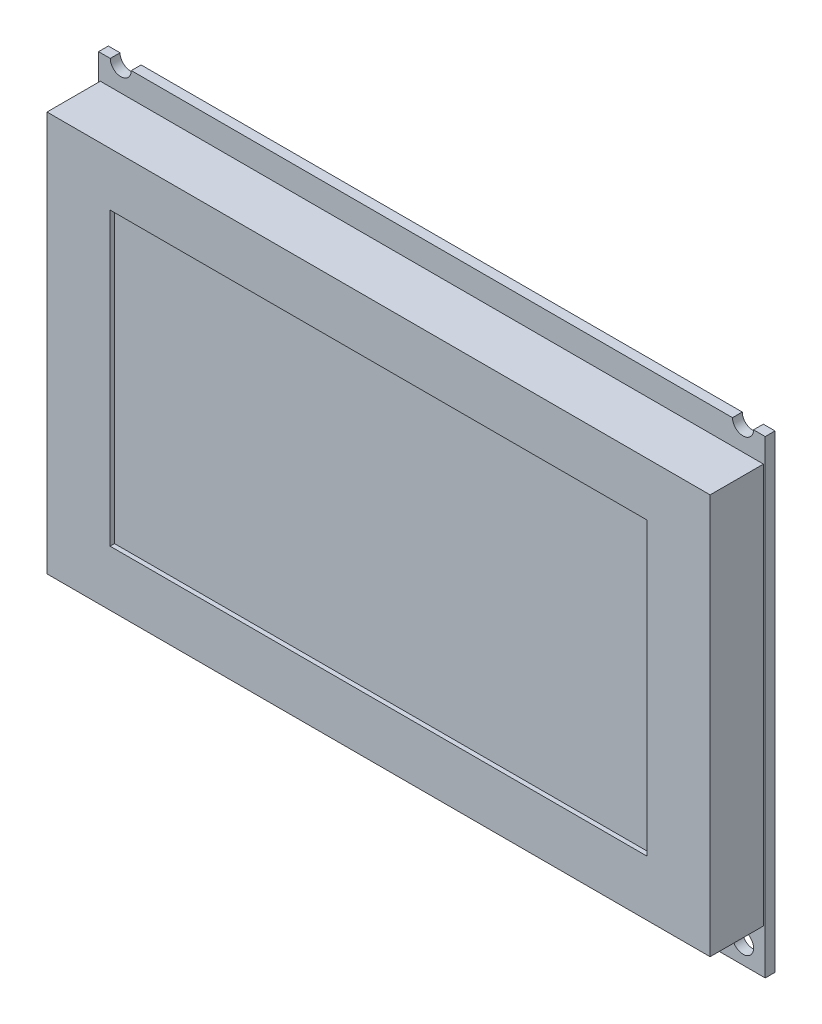
SolidWorks part; units mm, degrees
ref_plane "Front Plane" through (0, 0, 0) normal (0, 0, 1) x (1, 0, 0)
ref_plane "Top Plane" through (0, 0, 0) normal (0, 1, 0) x (1, 0, 0)
ref_plane "Right Plane" through (0, 0, 0) normal (1, 0, 0) x (0, 0, -1)
sketch "Sketch1" plane through (0, 0, 0) normal (0, 0, 1) x (1, 0, 0)
  line L1 (-37.5, 26.375) -> (37.5, 26.375)
  line L2 (-37.5, 26.375) -> (-37.5, -26.375)
  line L3 (-37.5, -26.375) -> (37.5, -26.375)
  line L4 (37.5, 26.375) -> (37.5, -26.375)
  line L5 (-37.5, 26.375) -> (37.5, -26.375) construction
  line L6 (-37.5, -26.375) -> (37.5, 26.375) construction
  point P0 (0, 0)
  dimension "D1" = 52.75
  dimension "D2" = 75
extrude "Boss-Extrude1" add sketch "Sketch1" along normal blind 1.1
sketch "Sketch2" plane through (0, 0, 1.1) normal (0, 0, 1) x (1, 0, 0)
  line L0 (-37.5, -26.375) -> (37.5, -26.375) construction
  line L1 (37.5, 26.375) -> (-37.5, 26.375) construction
  line L2 (-35, -24.125) -> (35, -24.125) construction
  circle A0 centre (-35, -24.125) radius 1.185
  circle A1 centre (35, -24.125) radius 1.185
  circle A2 centre (35, 26.375) radius 1.185
  circle A3 centre (-35, 26.375) radius 1.185
  point P12 (0, -24.125)
  dimension "D1" = 2.37
  dimension "D2" = 70
  dimension "D3" = 2.25
extrude "Cut-Extrude1" cut sketch "Sketch2" against normal through all
sketch "Sketch3" plane through (0, 0, 1.1) normal (0, 0, 1) x (1, 0, 0)
  line L0 (33.815, 26.375) -> (-33.815, 26.375) construction
  line L1 (-37.3, 23.595) -> (37.3, 23.595)
  line L2 (-37.3, 23.595) -> (-37.3, -21.405)
  line L3 (-37.3, -21.405) -> (37.3, -21.405)
  line L4 (37.3, 23.595) -> (37.3, -21.405)
  line L5 (-37.3, 23.595) -> (37.3, -21.405) construction
  line L6 (-37.3, -21.405) -> (37.3, 23.595) construction
  point P0 (0, 1.095)
  dimension "D1" = 45
  dimension "D2" = 74.6
  dimension "D3" = 2.78
extrude "Boss-Extrude2" add sketch "Sketch3" along normal blind 6
sketch "Sketch4" plane through (0, 0, 7.1) normal (0, 0, 1) x (1, 0, 0)
  line L0 (37.3, -21.405) -> (37.3, 23.595) construction
  line L1 (-30.2, 17.595) -> (30.2, 17.595)
  line L2 (-30.2, 17.595) -> (-30.2, -15.155)
  line L3 (-30.2, -15.155) -> (30.2, -15.155)
  line L4 (30.2, 17.595) -> (30.2, -15.155)
  line L5 (-30.2, 17.595) -> (30.2, -15.155) construction
  line L6 (-30.2, -15.155) -> (30.2, 17.595) construction
  line L7 (-37.3, 23.595) -> (-37.3, -21.405) construction
  line L8 (37.3, 23.595) -> (-37.3, 23.595) construction
  line L9 (-37.3, -21.405) -> (37.3, -21.405) construction
  point P0 (0, 1.22)
  dimension "D1" = 7.1
  dimension "D2" = 7.1
  dimension "D3" = 6
  dimension "D4" = 6.25
extrude "Cut-Extrude2" cut sketch "Sketch4" against normal blind 0.5
